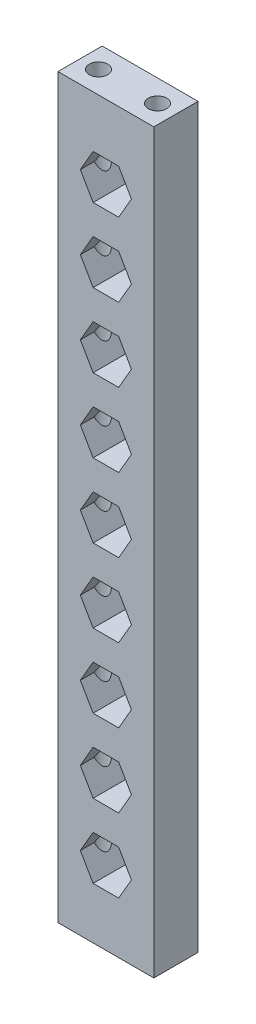
SolidWorks part; units mm, degrees
material "6061 合金"
ref_plane "前视基准面" through (0, 0, 0) normal (0, 0, 1) x (1, 0, 0)
ref_plane "上视基准面" through (0, 0, 0) normal (0, 1, 0) x (1, 0, 0)
ref_plane "右视基准面" through (0, 0, 0) normal (1, 0, 0) x (0, 0, -1)
sketch "草图1" plane through (0, 0, 0) normal (0, 1, 0) x (1, 0, 0)
  line L1 (6.5, 3) -> (-6.5, 3)
  line L2 (6.5, 3) -> (6.5, -3)
  line L3 (6.5, -3) -> (-6.5, -3)
  line L4 (-6.5, 3) -> (-6.5, -3)
  line L5 (6.5, 3) -> (-6.5, -3) construction
  line L6 (6.5, -3) -> (-6.5, 3) construction
  point P0 (0, 0)
  dimension "D1" = 13
  dimension "D2" = 6
extrude "凸台-拉伸1" add sketch "草图1" along normal blind 100
sketch "草图2" plane through (0, 0, -3) normal (0, 0, -1) x (-1, 0, 0)
  line L0 (-6.5, 0) -> (6.5, 0) construction
  line L1 (-1.7321, 13) -> (-3.4641, 10)
  line L2 (-3.4641, 10) -> (-1.7321, 7)
  line L3 (-1.7321, 7) -> (1.7321, 7)
  line L4 (1.7321, 7) -> (3.4641, 10)
  line L5 (3.4641, 10) -> (1.7321, 13)
  line L6 (1.7321, 13) -> (-1.7321, 13)
  line L7 (-1.7321, 23) -> (-3.4641, 20)
  line L8 (-3.4641, 20) -> (-1.7321, 17)
  line L9 (-1.7321, 17) -> (1.7321, 17)
  line L10 (1.7321, 17) -> (3.4641, 20)
  line L11 (3.4641, 20) -> (1.7321, 23)
  line L12 (1.7321, 23) -> (-1.7321, 23)
  line L13 (-1.7321, 33) -> (-3.4641, 30)
  line L14 (-3.4641, 30) -> (-1.7321, 27)
  line L15 (-1.7321, 27) -> (1.7321, 27)
  line L16 (1.7321, 27) -> (3.4641, 30)
  line L17 (3.4641, 30) -> (1.7321, 33)
  line L18 (1.7321, 33) -> (-1.7321, 33)
  line L19 (-1.7321, 43) -> (-3.4641, 40)
  line L20 (-3.4641, 40) -> (-1.7321, 37)
  line L21 (-1.7321, 37) -> (1.7321, 37)
  line L22 (1.7321, 37) -> (3.4641, 40)
  line L23 (3.4641, 40) -> (1.7321, 43)
  line L24 (1.7321, 43) -> (-1.7321, 43)
  line L25 (-1.7321, 53) -> (-3.4641, 50)
  line L26 (-3.4641, 50) -> (-1.7321, 47)
  line L27 (-1.7321, 47) -> (1.7321, 47)
  line L28 (1.7321, 47) -> (3.4641, 50)
  line L29 (3.4641, 50) -> (1.7321, 53)
  line L30 (1.7321, 53) -> (-1.7321, 53)
  line L31 (-1.7321, 63) -> (-3.4641, 60)
  line L32 (-3.4641, 60) -> (-1.7321, 57)
  line L33 (-1.7321, 57) -> (1.7321, 57)
  line L34 (1.7321, 57) -> (3.4641, 60)
  line L35 (3.4641, 60) -> (1.7321, 63)
  line L36 (1.7321, 63) -> (-1.7321, 63)
  line L37 (-1.7321, 73) -> (-3.4641, 70)
  line L38 (-3.4641, 70) -> (-1.7321, 67)
  line L39 (-1.7321, 67) -> (1.7321, 67)
  line L40 (1.7321, 67) -> (3.4641, 70)
  line L41 (3.4641, 70) -> (1.7321, 73)
  line L42 (1.7321, 73) -> (-1.7321, 73)
  line L43 (-1.7321, 83) -> (-3.4641, 80)
  line L44 (-3.4641, 80) -> (-1.7321, 77)
  line L45 (-1.7321, 77) -> (1.7321, 77)
  line L46 (1.7321, 77) -> (3.4641, 80)
  line L47 (3.4641, 80) -> (1.7321, 83)
  line L48 (1.7321, 83) -> (-1.7321, 83)
  line L49 (-1.7321, 93) -> (-3.4641, 90)
  line L50 (-3.4641, 90) -> (-1.7321, 87)
  line L51 (-1.7321, 87) -> (1.7321, 87)
  line L52 (1.7321, 87) -> (3.4641, 90)
  line L53 (3.4641, 90) -> (1.7321, 93)
  line L54 (1.7321, 93) -> (-1.7321, 93)
  line L55 (6.5, 50) -> (-6.5, 50) construction
  line L56 (6.5, 100) -> (6.5, 0) construction
  line L57 (-6.5, 100) -> (-6.5, 0) construction
  circle A0 centre (0, 10) radius 3 construction
  circle A1 centre (0, 20) radius 3 construction
  circle A2 centre (0, 30) radius 3 construction
  circle A3 centre (0, 40) radius 3 construction
  circle A4 centre (0, 50) radius 3 construction
  circle A5 centre (0, 60) radius 3 construction
  circle A6 centre (0, 70) radius 3 construction
  circle A7 centre (0, 80) radius 3 construction
  circle A8 centre (0, 90) radius 3 construction
  point P80 (0, 49.1593)
  point P81 (-6.5, 50)
  dimension "D2" = 6
  dimension "D1" = 9
extrude "切除-拉伸1" cut sketch "草图2" against normal through all both and the other way through all
hole_wizard "M3 螺纹孔1" positions "草图6" profile "草图5" tap size "M3" standard "GB" end condition through all
sketch "草图6" plane through (0, 0, 0) normal (0, -1, 0) x (-1, 0, 0)
  line L0 (4, 0) -> (-4, 0) construction
  point P0 (4, 0)
  point P2 (-4, 0)
  dimension "D1" = 8
sketch "草图5" plane through (-4, 0, 0) normal (1, 0, 0) x (0, 0, -1)
  line L0 (0, 0) -> (0, 100)
  line L1 (0, 100) -> (1.25, 100)
  line L2 (1.25, 100) -> (1.25, 0.275)
  line L3 (1.25, 0.275) -> (1.525, 0)
  line L5 (1.525, 0) -> (0, 0)
  line L6 (-1.25, 0.275) -> (-1.525, 0) construction
  line L11 (0, -6.35) -> (0, 107.95) construction
  dimension "通孔螺纹孔钻头直径" = 2.5
  dimension "通孔螺纹孔钻头深度" = 100
  dimension "近端锥形沉头孔直径" = 3.05
  dimension "近端锥形沉头孔角度" = 90
cosmetic thread "孔螺蚊线1" parameters "D2"=3
cosmetic thread "孔螺蚊线2" parameters "D2"=3
